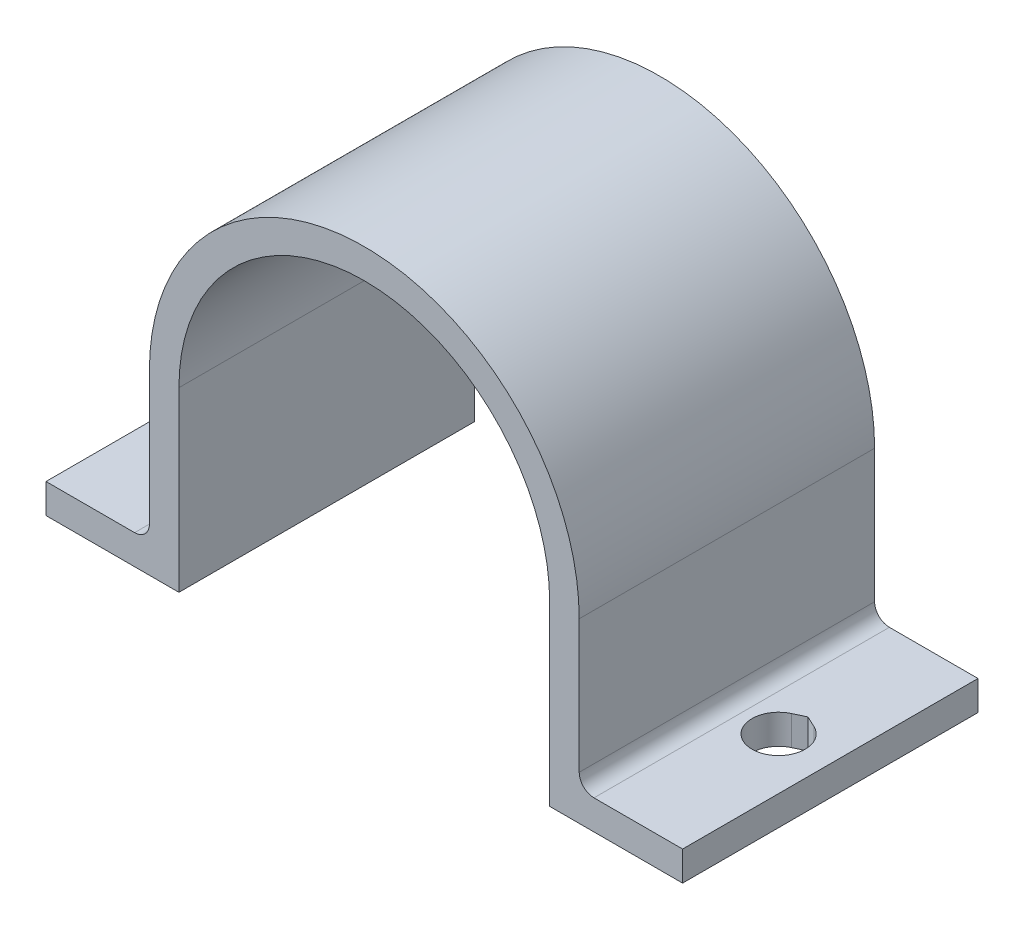
SolidWorks part; units mm, degrees
ref_plane "Alzado" through (0, 0, 0) normal (0, 0, 1) x (1, 0, 0)
ref_plane "Planta" through (0, 0, 0) normal (0, 1, 0) x (1, 0, 0)
ref_plane "Vista lateral" through (0, 0, 0) normal (1, 0, 0) x (0, 0, -1)
sketch "Croquis1" plane through (0, 0, 0) normal (0, 0, 1) x (1, 0, 0)
  line L0 (-12.55, 0) -> (-21.55, 0)
  line L1 (-21.55, 0) -> (-21.55, 2)
  line L2 (-21.55, 2) -> (-14.55, 2)
  line L3 (0, 26.55) -> (0, 24.55)
  line L7 (-12.55, 0) -> (-12.55, 12)
  line L8 (-14.55, 2) -> (-14.55, 12)
  line L9 (14.55, 2) -> (14.55, 12)
  line L10 (12.55, 0) -> (12.55, 12)
  line L11 (21.55, 2) -> (14.55, 2)
  line L12 (21.55, 0) -> (21.55, 2)
  line L13 (12.55, 0) -> (21.55, 0)
  arc A2 (-12.55, 12) -> (12.55, 12) centre (0, 12) cw
  arc A3 (-14.55, 12) -> (14.55, 12) centre (0, 12) cw
  point P9 (-1.496, 10.323)
  point P10 (-7.5415, 12)
  point P11 (-10.5785, 10.323)
  point P13 (-7.4946, 12.0362)
  point P14 (-10.147, 12.8817)
  dimension "D2" = 12
  dimension "D4" = 2
  dimension "D5" = 12.55
  dimension "D6" = 2
  dimension "D1" = 2
  dimension "D3" = 7
extrude "Saliente-Extruir1" add sketch "Croquis1" along normal blind 20
hole_wizard "Taladro de margen para M31" positions "Croquis2" profile "Croquis3" hole size "M3" standard "Ansi Metric" end condition up to next
sketch "Croquis2" plane through (0, 2, 0) normal (0, 1, 0) x (1, 0, 0)
  line L0 (-18.05, 0) -> (-18.05, -20) construction
  line L1 (-21.55, 0) -> (-14.55, 0) construction
  line L2 (-21.55, -20) -> (-14.55, -20) construction
  line L5 (-21.55, -10) -> (21.55, -10) construction
  line L14 (18.05, 0) -> (18.05, -20) construction
  line L48 (21.55, -20) -> (21.55, 0) construction
  line L49 (21.55, 0) -> (14.55, 0) construction
  line L50 (21.55, -20) -> (14.55, -20) construction
  point P12 (-21.55, -20)
  point P13 (-21.55, 0)
  point P27 (-18.05, -10)
  point P38 (18.05, -10)
  point P41 (-14.55, -20)
  point P42 (-14.55, 0)
  point P43 (-14.55, -20)
  point P44 (-14.55, 0)
  point P45 (-21.55, -20)
  point P46 (-21.55, 0)
  point P47 (-12.55, -20)
  point P48 (-12.55, 0)
  point P49 (-12.55, -20)
  point P50 (-12.55, 0)
  point P51 (12.55, -20)
  point P52 (12.55, 0)
  point P53 (12.55, -20)
  point P54 (12.55, 0)
  point P55 (21.55, -20)
  point P56 (21.55, 0)
  point P57 (21.55, -20)
  point P58 (21.55, 0)
  point P59 (14.55, -20)
  point P60 (14.55, 0)
  point P61 (14.55, -20)
  point P62 (14.55, 0)
  point P63 (21.55, -20)
  point P64 (14.55, -20)
  point P65 (12.55, -20)
  point P66 (21.55, -20)
  point P67 (-12.55, -20)
  point P68 (12.55, -20)
  point P69 (-12.55, -20)
  point P70 (-21.55, -20)
  point P71 (-21.55, -20)
  point P72 (-14.55, -20)
  point P73 (-14.55, -20)
  point P74 (14.55, -20)
  point P75 (21.55, 0)
  point P76 (14.55, 0)
  point P77 (12.55, 0)
  point P78 (21.55, 0)
  point P79 (12.55, 0)
  point P80 (-12.55, 0)
  point P81 (-12.55, 0)
  point P82 (-21.55, 0)
  point P83 (-21.55, 0)
  point P84 (-14.55, 0)
  point P85 (14.55, 0)
  point P86 (-14.55, 0)
  point P87 (-12.55, 0)
  point P88 (-21.55, 0)
  point P89 (-21.55, 0)
  point P90 (-14.55, 0)
  point P91 (21.55, 0)
  point P92 (14.55, 0)
  point P93 (12.55, 0)
  point P94 (21.55, 0)
  point P95 (-18.05, -11.8)
  point P96 (-18.05, -8.0114)
  point P97 (-18.8151, -8.3707)
  point P98 (-18.05, -8.0114)
  point P99 (-17.2849, -8.3707)
  point P100 (-18.05, -8.0114)
  point P101 (21.55, -10)
  point P104 (18.7329, -3.8077)
  point P105 (18.05, 0)
  point P108 (18.05, -20)
sketch "Croquis3" plane through (18.05, 2, 10) normal (1, 0, 0) x (0, 0, 1)
  line L0 (0, 0) -> (0, 2)
  line L1 (0, 2) -> (1.8, 2)
  line L2 (1.8, 2) -> (1.8, 0)
  line L5 (1.8, 0) -> (0, 0)
  line L11 (0, -6.35) -> (0, 107.95) construction
  dimension "Diámetro de taladro hasta el siguiente" = 3.6
  dimension "Profundidad de taladro hasta el siguiente" = 2
fillet "Redondeo1" radius 1 2 edges at (14.55, 2, 10) (-14.55, 2, 10)
sketch "Croquis4" plane through (0, 2, 0) normal (0, 1, 0) x (1, 0, 0)
  line L0 (-18.05, -11.8) -> (-18.05, -8.0114) construction
  line L1 (-18.8151, -8.3707) -> (-18.05, -8.0114)
  line L2 (-17.2849, -8.3707) -> (-18.05, -8.0114)
  circle A0 centre (-18.05, -10) radius 1.8 construction
  arc A1 (-18.8151, -8.3707) -> (-17.2849, -8.3707) centre (-18.05, -10) cw
  point P6 (-17.9119, -8.0114)
extrude "Cortar-Extruir1" cut sketch "Croquis4" against normal up to next
mirror "Simetría1" about plane through (0, 0, 0) normal (1, 0, 0) of "Cortar-Extruir1"
